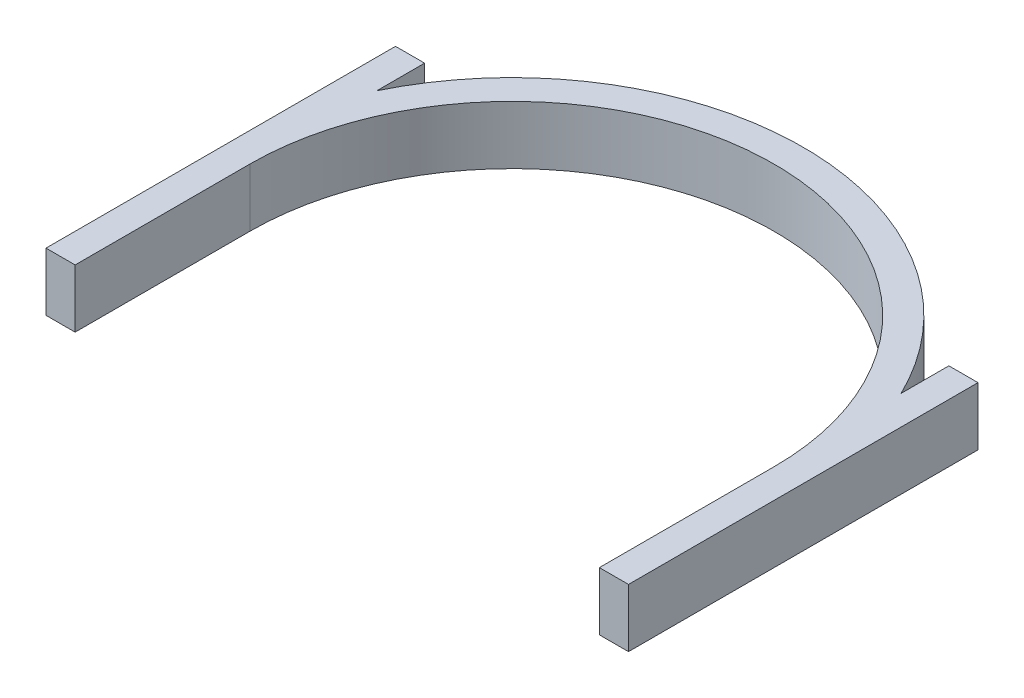
SolidWorks part; units mm, degrees
ref_plane "Front" through (0, 0, 0) normal (0, 0, 1) x (1, 0, 0)
ref_plane "Top" through (0, 0, 0) normal (0, 1, 0) x (1, 0, 0)
ref_plane "Right" through (0, 0, 0) normal (1, 0, 0) x (0, 0, -1)
sketch "草图1" plane through (0, 0, 0) normal (0, 1, 0) x (1, 0, 0)
  line L0 (-56.6383, 0) -> (0, 0) construction
  line L1 (0, 0) -> (0, 68.2861) construction
  line L2 (-45, 0) -> (-45, -30)
  line L3 (-50, 30) -> (-45, 30)
  line L4 (-50, 30) -> (-50, -30)
  line L5 (-50, -30) -> (-45, -30)
  line L6 (-45, 30) -> (-45, 21.7945)
  line L7 (45, 30) -> (50, 30)
  line L8 (45, 30) -> (45, 21.7945)
  line L9 (45, -30) -> (50, -30)
  line L10 (50, 30) -> (50, -30)
  line L11 (45, 0) -> (45, -30)
  arc A1 (45, 0) -> (-45, 0) centre (0, 0) ccw
  arc A2 (45, 21.7945) -> (-45, 21.7945) centre (0, 0) ccw
  dimension "D2" = 5
  dimension "D3" = 60
  dimension "D5" = 50
  dimension "D6" = 5
  dimension "D7" = 60
  dimension "D8" = 30
extrude "凸台-拉伸1" add sketch "草图1" along normal blind 10
